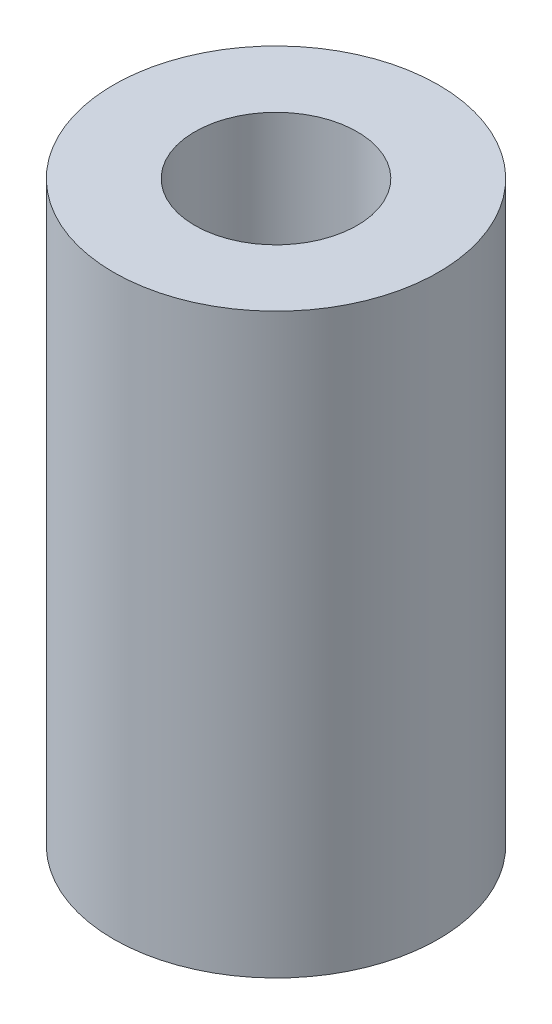
SolidWorks part; units mm, degrees
ref_plane "Спереди" through (0, 0, 0) normal (0, 0, 1) x (1, 0, 0)
ref_plane "Сверху" through (0, 0, 0) normal (0, 1, 0) x (1, 0, 0)
ref_plane "Справа" through (0, 0, 0) normal (1, 0, 0) x (0, 0, -1)
sketch "Эскиз1" plane through (0, 0, 0) normal (0, 1, 0) x (1, 0, 0)
  circle A0 centre (0, 0) radius 2.25
  circle A1 centre (0, 0) radius 4.5
  dimension "D1" = 4.5
  dimension "D2" = 9
extrude "Бобышка-Вытянуть1" add sketch "Эскиз1" along normal mid plane 16
